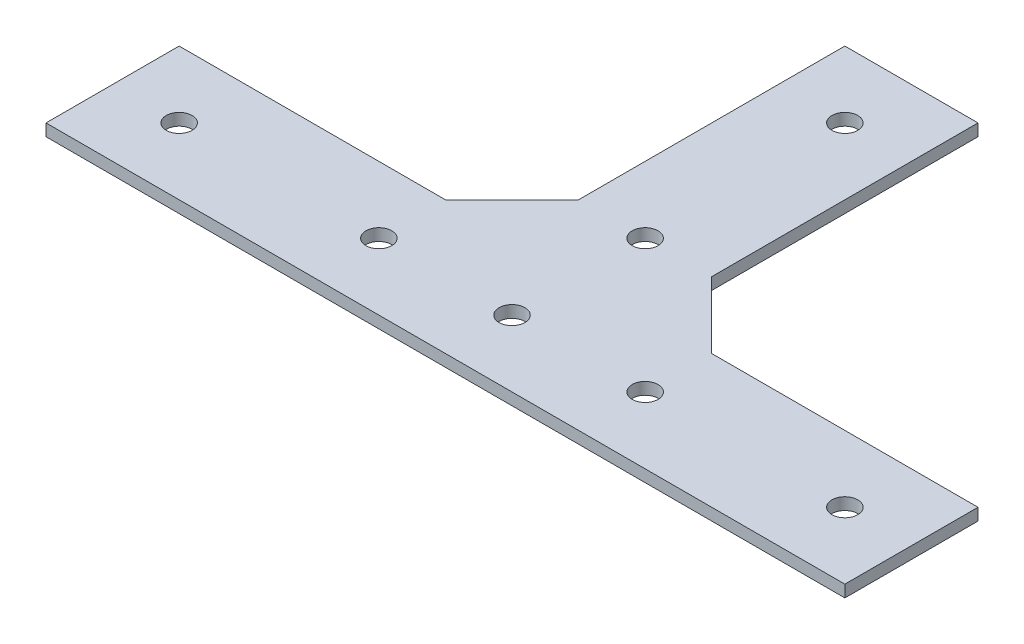
SolidWorks part; units mm, degrees
material "1060 Alloy"
ref_plane "Front Plane" through (0, 0, 0) normal (0, 0, 1) x (1, 0, 0)
ref_plane "Top Plane" through (0, 0, 0) normal (0, 1, 0) x (1, 0, 0)
ref_plane "Right Plane" through (0, 0, 0) normal (1, 0, 0) x (0, 0, -1)
sketch "Sketch1" plane through (0, 0, 0) normal (0, 1, 0) x (1, 0, 0)
  line L0 (25.4, 38.1) -> (38.1, 25.4)
  line L1 (0, 0) -> (88.9, 0)
  line L2 (0, 88.9) -> (0, 0)
  line L3 (12.7, 88.9) -> (12.7, 0) construction
  line L8 (38.1, 25.4) -> (88.9, 25.4)
  line L9 (88.9, 0) -> (88.9, 25.4)
  line L12 (0, 88.9) -> (25.4, 88.9)
  line L13 (25.4, 38.1) -> (25.4, 88.9)
  dimension "D1" = 25.4
  dimension "D2" = 88.9
  dimension "D3" = 50.8
extrude "Boss-Extrude1" add sketch "Sketch1" along normal blind 2.286
ref_plane "Plane1" through (12.7, 0, 0) normal (-1, 0, 0) x (0, 0, 1)
mirror "Mirror1" about plane through (12.7, 0, 0) normal (-1, 0, 0) of "Boss-Extrude1"
sketch "Sketch3" plane through (0, 2.286, 0) normal (0, 1, 0) x (1, 0, 0)
  line L0 (0, 12.7) -> (88.9, 12.7) construction
  line L1 (0, 88.9) -> (0, 38.1) construction
  line L2 (88.9, 0) -> (88.9, 25.4) construction
  line L3 (12.7, 88.9) -> (12.7, 0) construction
  line L4 (25.4, 88.9) -> (0, 88.9) construction
  line L5 (-63.5, 0) -> (88.9, 0) construction
  circle A0 centre (76.2, 12.7) radius 2.4638
  circle A1 centre (12.7, 12.7) radius 2.4638
  circle A2 centre (12.7, 76.2) radius 2.4638
  circle A3 centre (12.7, 38.1) radius 2.4638
  circle A4 centre (38.1, 12.7) radius 2.4638
  dimension "D1" = 4.9276
  dimension "D2" = 12.7
  dimension "D3" = 12.7
  dimension "D4" = 25.4
  dimension "D5" = 25.4
extrude "Cut-Extrude2" cut sketch "Sketch3" against normal through all
mirror "Mirror2" about plane through (12.7, 0, 0) normal (-1, 0, 0) of "Cut-Extrude2"
